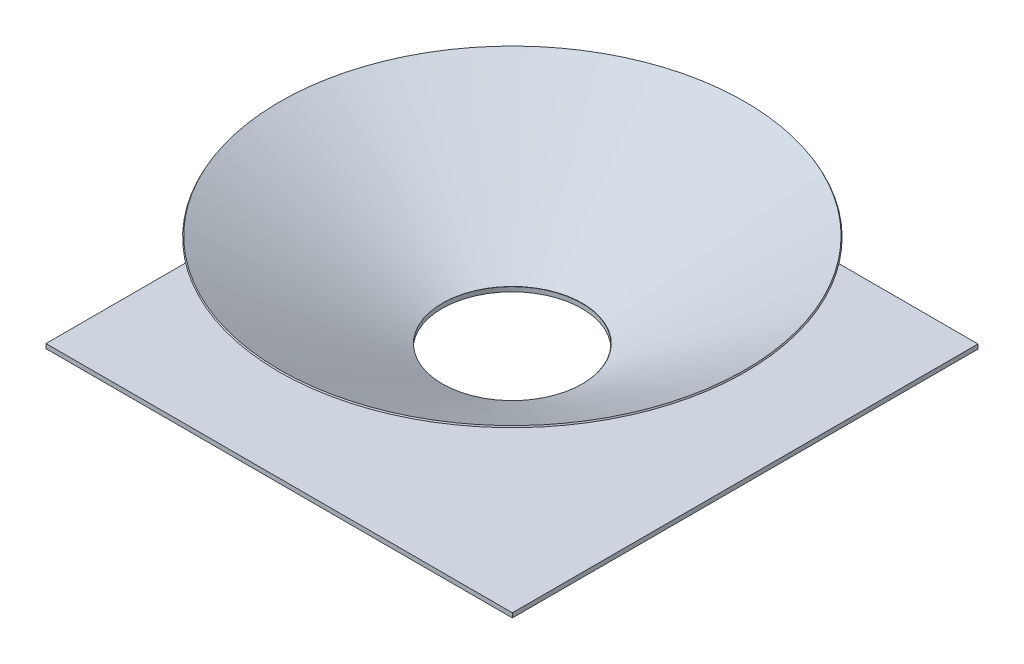
SolidWorks part; units mm, degrees
ref_plane "Front Plane" through (0, 0, 0) normal (0, 0, 1) x (1, 0, 0)
ref_plane "Top Plane" through (0, 0, 0) normal (0, 1, 0) x (1, 0, 0)
ref_plane "Right Plane" through (0, 0, 0) normal (1, 0, 0) x (0, 0, -1)
sketch "Sketch1" plane through (0, 0, 0) normal (0, 0, 1) x (1, 0, 0)
  line L0 (-48.8837, 0) -> (-156.25, 61.6327)
  line L1 (-156.25, 61.6327) -> (-155.7522, 62.5)
  line L2 (-155.7522, 62.5) -> (-46.875, 0)
  line L3 (-48.8837, 0) -> (-46.875, 0)
  line L4 (0, 0) -> (0, 38.049) construction
  line L5 (0, 0) -> (-37.9362, 0) construction
  dimension "D1" = 46.875
  dimension "D2" = 156.25
  dimension "D3" = 1
  dimension "D4" = 62.5
revolve "Revolve1" add sketch "Sketch1" angle 360 about L4
sketch "Sketch2" plane through (0, 0, 0) normal (0, 1, 0) x (1, 0, 0)
  line L0 (-156.25, -156.25) -> (156.25, -156.25)
  line L1 (-156.25, -156.25) -> (-156.25, 155.7522)
  line L2 (156.25, -156.25) -> (156.25, 155.7522)
  line L3 (-156.25, 155.7522) -> (156.25, 155.7522)
  line L4 (-156.25, -156.25) -> (156.25, 155.7522) construction
  line L5 (156.25, -156.25) -> (-156.25, 155.7522) construction
  circle A0 centre (0, -0.2489) radius 46.875
  circle A1 centre (0, 0) radius 156.25 construction
  circle A2 centre (0, 0) radius 155.7522 construction
  point P1 (0, -0.2489)
  dimension "D1" = 93.75
extrude "Boss-Extrude1" add sketch "Sketch2" against normal blind 3 separate body
